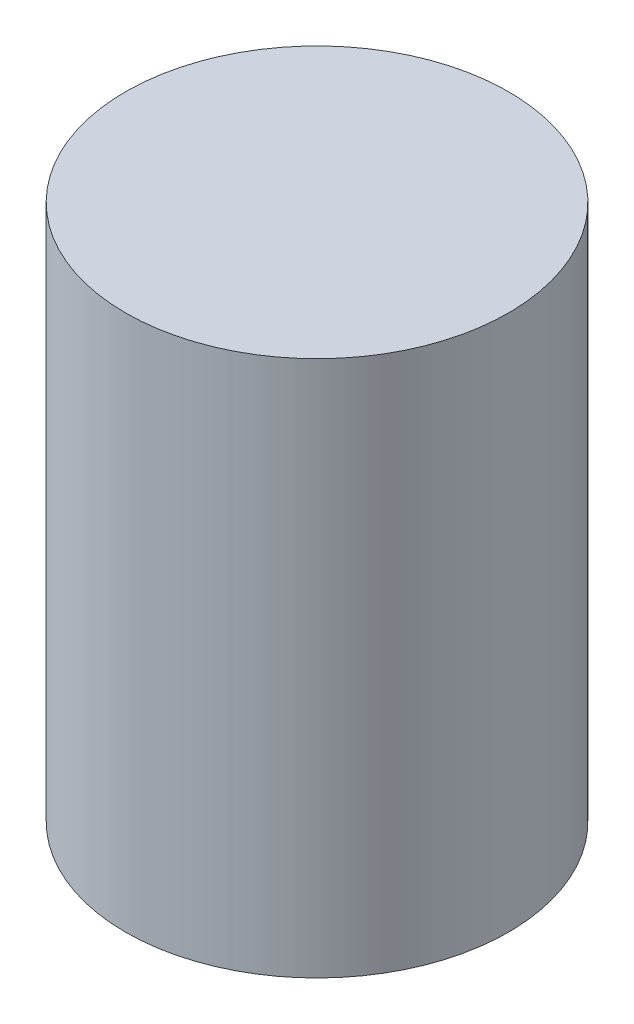
SolidWorks part; units mm, degrees
ref_plane "Front Plane" through (0, 0, 0) normal (0, 0, 1) x (1, 0, 0)
ref_plane "Top Plane" through (0, 0, 0) normal (0, 1, 0) x (1, 0, 0)
ref_plane "Right Plane" through (0, 0, 0) normal (1, 0, 0) x (0, 0, -1)
other "Configuration Table"
sketch "Sketch1" plane through (0, 0, 0) normal (0, 1, 0) x (1, 0, 0)
  circle A0 centre (150, 650) radius 50
extrude "PACK_vakum_tanki_1L_D100" add sketch "Sketch1" along normal blind 140 from offset 300 separate body
